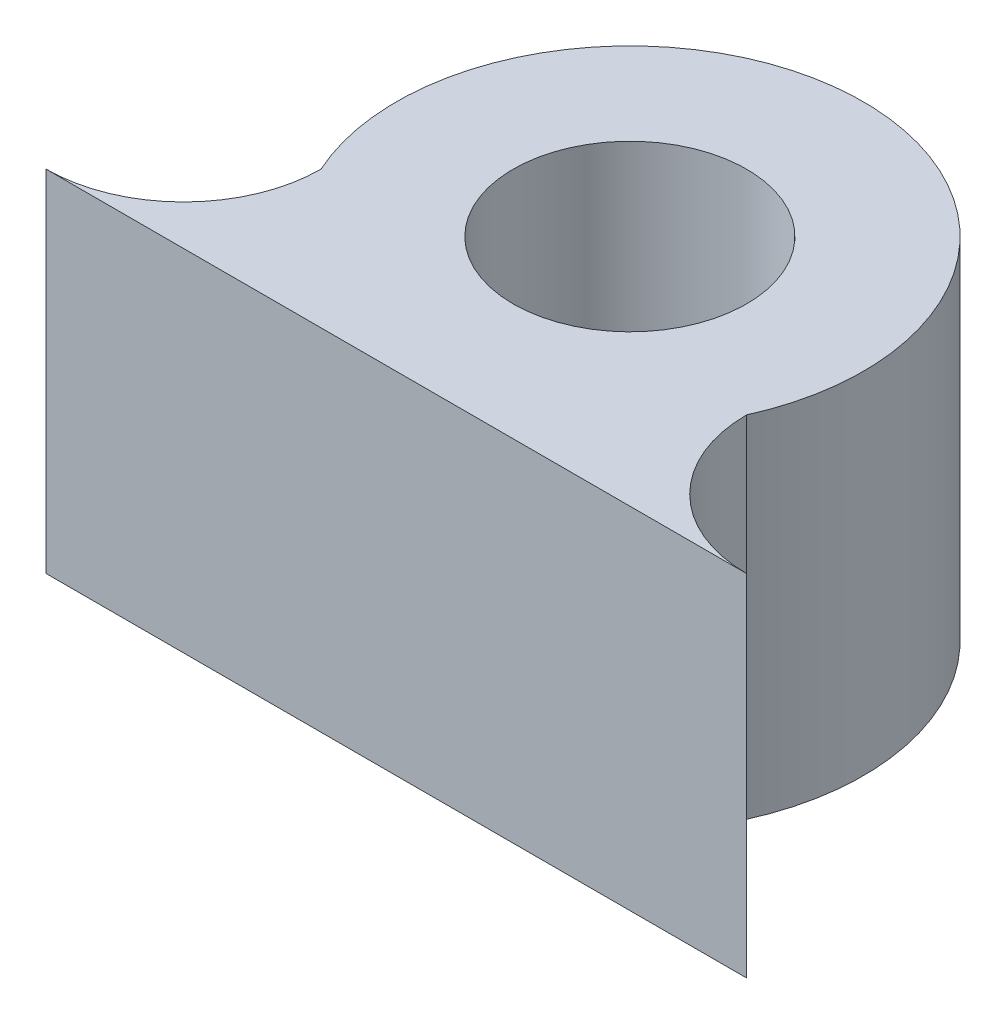
SolidWorks part; units mm, degrees
ref_plane "前视基准面" through (0, 0, 0) normal (0, 0, 1) x (1, 0, 0)
ref_plane "上视基准面" through (0, 0, 0) normal (0, 1, 0) x (1, 0, 0)
ref_plane "右视基准面" through (0, 0, 0) normal (1, 0, 0) x (0, 0, -1)
other "Configuration Table"
sketch "草图1" plane through (0, 0, 0) normal (0, 1, 0) x (1, 0, 0)
  circle A0 centre (0, 0) radius 2
  circle A1 centre (0, 0) radius 1
  dimension "D1" = 4
  dimension "D2" = 2
extrude "凸台-拉伸1" add sketch "草图1" along normal blind 3
sketch "草图2" plane through (0, 3, 0) normal (0, 1, 0) x (1, 0, 0)
  line L0 (0, -2) -> (-3, -2)
  line L1 (0, -2) -> (3, -2)
  circle A0 centre (0, 0) radius 2 construction
  arc A1 (-3, -2) -> (-1.8229, -0.8229) centre (-3, -0.8229) ccw
  arc A2 (3, -2) -> (1.8229, -0.8229) centre (3, -0.8229) cw
  circle A4 centre (0, 0) radius 2
  arc A5 (-1.8229, -0.8229) -> (1.8229, -0.8229) centre (0, 0) ccw
  circle M4 centre (0, 0) radius 2
  dimension "D3" = 0
  dimension "D1" = 3
  dimension "D2" = 3
extrude "凸台-拉伸2" add sketch "草图2" against normal blind 3 contours A1 L0 M4 | L1 A2 M4
